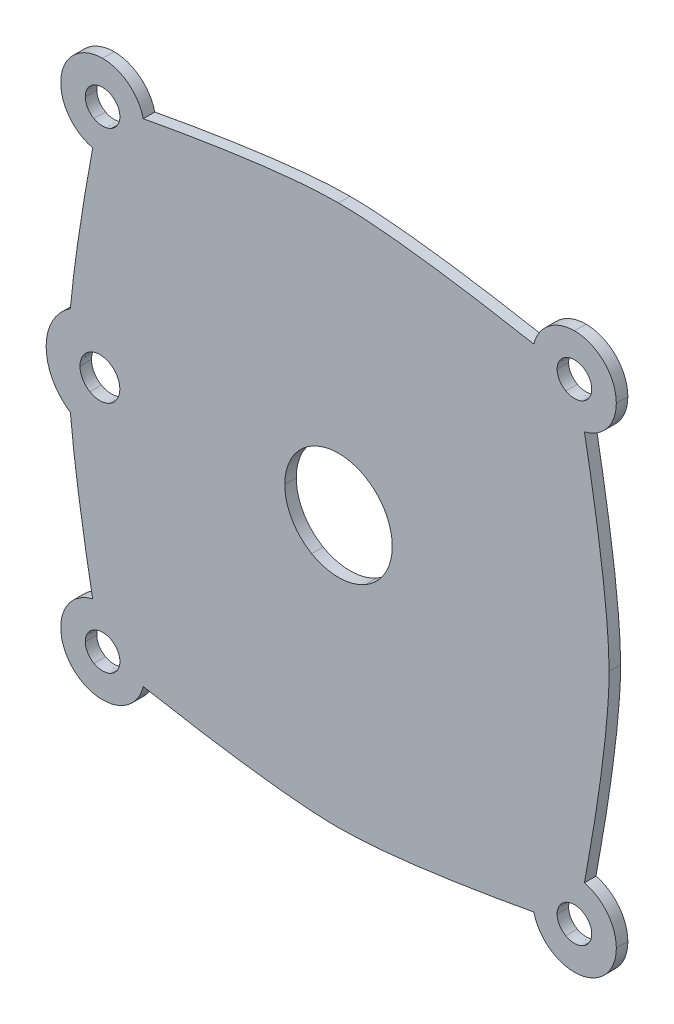
SolidWorks part; units mm, degrees
ref_plane "Front Plane" through (0, 0, 0) normal (0, 0, 1) x (1, 0, 0)
ref_plane "Top Plane" through (0, 0, 0) normal (0, 1, 0) x (1, 0, 0)
ref_plane "Right Plane" through (0, 0, 0) normal (1, 0, 0) x (0, 0, -1)
sketch "Model" plane through (0, 0, 0) normal (0, 0, 1) x (1, 0, 0)
  spline S0 degree 3 poles (51.3556, 215.6759) (48.1704, 215.6759) (45.5877, 213.0932) (45.5877, 209.908) knots 0 0 0 0 1 1 1 1
  spline S1 degree 3 poles (45.5877, 209.908) (45.5877, 207.1926) (47.4617, 204.9204) (49.9886, 204.3076) knots 0 0 0 0 1 1 1 1
  spline S2 degree 3 poles (49.9886, 204.3076) (48.974, 198.8606) (47.5466, 190.5406) (46.9106, 183.5819) knots 0 0 0 0 1 1 1 1
  spline S3 degree 3 poles (46.9106, 183.5819) (44.902, 182.2575) (43.5769, 179.9855) (43.5769, 177.3995) knots 0 0 0 0 1 1 1 1
  spline S4 degree 3 poles (43.5769, 177.3995) (43.5769, 174.8136) (44.902, 172.5327) (46.9106, 171.2083) knots 0 0 0 0 1 1 1 1
  spline S5 degree 3 poles (46.9106, 171.2083) (47.5443, 164.2507) (48.9657, 155.9401) (49.9798, 150.4914) knots 0 0 0 0 1 1 1 1
  spline S6 degree 3 poles (49.9798, 150.4914) (47.4567, 149.8759) (45.5877, 147.6036) (45.5877, 144.891) knots 0 0 0 0 1 1 1 1
  spline S7 degree 3 poles (45.5877, 144.891) (45.5877, 141.7058) (48.1704, 139.1231) (51.3556, 139.1231) knots 0 0 0 0 1 1 1 1
  spline S8 degree 3 poles (51.3556, 139.1231) (54.0682, 139.1231) (56.3405, 140.9922) (56.956, 143.5152) knots 0 0 0 0 1 1 1 1
  spline S9 degree 3 poles (56.956, 143.5152) (64.1681, 142.173) (76.4059, 140.1197) (83.8641, 140.1197) knots 0 0 0 0 1 1 1 1
  spline S10 degree 3 poles (83.8641, 140.1197) (91.3223, 140.1197) (103.5601, 142.173) (110.7722, 143.5152) knots 0 0 0 0 1 1 1 1
  spline S11 degree 3 poles (110.7722, 143.5152) (111.3879, 140.9924) (113.6601, 139.1231) (116.3726, 139.1231) knots 0 0 0 0 1 1 1 1
  spline S12 degree 3 poles (116.3726, 139.1231) (119.5578, 139.1231) (122.1405, 141.7058) (122.1405, 144.891) knots 0 0 0 0 1 1 1 1
  spline S13 degree 3 poles (122.1405, 144.891) (122.1405, 147.6013) (120.2682, 149.8736) (117.7484, 150.4914) knots 0 0 0 0 1 1 1 1
  spline S14 degree 3 poles (117.7484, 150.4914) (119.0906, 157.7035) (121.1439, 169.9413) (121.1439, 177.3995) knots 0 0 0 0 1 1 1 1
  spline S15 degree 3 poles (121.1439, 177.3995) (121.1439, 184.8577) (119.0906, 197.0955) (117.7484, 204.3076) knots 0 0 0 0 1 1 1 1
  spline S16 degree 3 poles (117.7484, 204.3076) (120.268, 204.9255) (122.1405, 207.1978) (122.1405, 209.908) knots 0 0 0 0 1 1 1 1
  spline S17 degree 3 poles (122.1405, 209.908) (122.1405, 213.0932) (119.5578, 215.6759) (116.3726, 215.6759) knots 0 0 0 0 1 1 1 1
  spline S18 degree 3 poles (116.3726, 215.6759) (113.6624, 215.6759) (111.3901, 213.8035) (110.7722, 211.2838) knots 0 0 0 0 1 1 1 1
  spline S19 degree 3 poles (110.7722, 211.2838) (103.5601, 212.626) (91.3223, 214.6793) (83.8641, 214.6793) knots 0 0 0 0 1 1 1 1
  spline S20 degree 3 poles (83.8641, 214.6793) (76.4044, 214.6793) (64.1668, 212.6181) (56.956, 211.275) knots 0 0 0 0 1 1 1 1
  spline S21 degree 3 poles (56.956, 211.275) (56.3413, 213.7991) (54.069, 215.6759) (51.3556, 215.6759) knots 0 0 0 0 1 1 1 1
  spline S22 degree 3 poles (53.7356, 209.9047) (53.7356, 209.0798) (53.2809, 208.3176) (52.5427, 207.9052) knots 0 0 0 0 1 1 1 1
  spline S23 degree 3 poles (52.5427, 207.9052) (51.8045, 207.4928) (50.8951, 207.4928) (50.1569, 207.9052) knots 0 0 0 0 1 1 1 1
  spline S24 degree 3 poles (50.1569, 207.9052) (49.4187, 208.3176) (48.964, 209.0798) (48.964, 209.9047) knots 0 0 0 0 1 1 1 1
  spline S25 degree 3 poles (48.964, 209.9047) (48.964, 210.7295) (49.4187, 211.4917) (50.1569, 211.9041) knots 0 0 0 0 1 1 1 1
  spline S26 degree 3 poles (50.1569, 211.9041) (50.8951, 212.3165) (51.8045, 212.3165) (52.5427, 211.9041) knots 0 0 0 0 1 1 1 1
  spline S27 degree 3 poles (52.5427, 211.9041) (53.2809, 211.4917) (53.7356, 210.7295) (53.7356, 209.9047) knots 0 0 0 0 1 1 1 1
  spline S28 degree 3 poles (118.7541, 144.8861) (118.7541, 144.0613) (118.2994, 143.2991) (117.5612, 142.8867) knots 0 0 0 0 1 1 1 1
  spline S29 degree 3 poles (117.5612, 142.8867) (116.823, 142.4743) (115.9136, 142.4743) (115.1754, 142.8867) knots 0 0 0 0 1 1 1 1
  spline S30 degree 3 poles (115.1754, 142.8867) (114.4373, 143.2991) (113.9825, 144.0613) (113.9825, 144.8861) knots 0 0 0 0 1 1 1 1
  spline S31 degree 3 poles (113.9825, 144.8861) (113.9825, 145.711) (114.4373, 146.4732) (115.1754, 146.8856) knots 0 0 0 0 1 1 1 1
  spline S32 degree 3 poles (115.1754, 146.8856) (115.9136, 147.298) (116.823, 147.298) (117.5612, 146.8856) knots 0 0 0 0 1 1 1 1
  spline S33 degree 3 poles (117.5612, 146.8856) (118.2994, 146.4732) (118.7541, 145.711) (118.7541, 144.8861) knots 0 0 0 0 1 1 1 1
  spline S34 degree 3 poles (53.7356, 144.8861) (53.7356, 144.0613) (53.2809, 143.2991) (52.5427, 142.8867) knots 0 0 0 0 1 1 1 1
  spline S35 degree 3 poles (52.5427, 142.8867) (51.8045, 142.4743) (50.8951, 142.4743) (50.1569, 142.8867) knots 0 0 0 0 1 1 1 1
  spline S36 degree 3 poles (50.1569, 142.8867) (49.4187, 143.2991) (48.964, 144.0613) (48.964, 144.8861) knots 0 0 0 0 1 1 1 1
  spline S37 degree 3 poles (48.964, 144.8861) (48.964, 145.711) (49.4187, 146.4732) (50.1569, 146.8856) knots 0 0 0 0 1 1 1 1
  spline S38 degree 3 poles (50.1569, 146.8856) (50.8951, 147.298) (51.8045, 147.298) (52.5427, 146.8856) knots 0 0 0 0 1 1 1 1
  spline S39 degree 3 poles (52.5427, 146.8856) (53.2809, 146.4732) (53.7356, 145.711) (53.7356, 144.8861) knots 0 0 0 0 1 1 1 1
  spline S40 degree 3 poles (118.7541, 209.9047) (118.7541, 209.0798) (118.2994, 208.3176) (117.5612, 207.9052) knots 0 0 0 0 1 1 1 1
  spline S41 degree 3 poles (117.5612, 207.9052) (116.823, 207.4928) (115.9136, 207.4928) (115.1754, 207.9052) knots 0 0 0 0 1 1 1 1
  spline S42 degree 3 poles (115.1754, 207.9052) (114.4373, 208.3176) (113.9825, 209.0798) (113.9825, 209.9047) knots 0 0 0 0 1 1 1 1
  spline S43 degree 3 poles (113.9825, 209.9047) (113.9825, 210.7295) (114.4373, 211.4917) (115.1754, 211.9041) knots 0 0 0 0 1 1 1 1
  spline S44 degree 3 poles (115.1754, 211.9041) (115.9136, 212.3165) (116.823, 212.3165) (117.5612, 211.9041) knots 0 0 0 0 1 1 1 1
  spline S45 degree 3 poles (117.5612, 211.9041) (118.2994, 211.4917) (118.7541, 210.7295) (118.7541, 209.9047) knots 0 0 0 0 1 1 1 1
  spline S46 degree 3 poles (53.7251, 177.3954) (53.7258, 176.4147) (53.203, 175.5083) (52.3538, 175.0177) knots 0 0 0 0 1 1 1 1
  spline S47 degree 3 poles (52.3538, 175.0177) (51.5046, 174.5272) (50.4582, 174.5272) (49.6091, 175.0177) knots 0 0 0 0 1 1 1 1
  spline S48 degree 3 poles (49.6091, 175.0177) (48.7599, 175.5083) (48.2371, 176.4147) (48.2377, 177.3954) knots 0 0 0 0 1 1 1 1
  spline S49 degree 3 poles (48.2377, 177.3954) (48.2371, 178.3761) (48.7599, 179.2825) (49.6091, 179.7731) knots 0 0 0 0 1 1 1 1
  spline S50 degree 3 poles (49.6091, 179.7731) (50.4582, 180.2636) (51.5046, 180.2636) (52.3538, 179.7731) knots 0 0 0 0 1 1 1 1
  spline S51 degree 3 poles (52.3538, 179.7731) (53.203, 179.2825) (53.7258, 178.3761) (53.7251, 177.3954) knots 0 0 0 0 1 1 1 1
  spline S52 degree 3 poles (91.2645, 177.3954) (91.2663, 174.7485) (89.8552, 172.3019) (87.5632, 170.978) knots 0 0 0 0 1 1 1 1
  spline S53 degree 3 poles (87.5632, 170.978) (85.2712, 169.654) (82.4469, 169.654) (80.1549, 170.978) knots 0 0 0 0 1 1 1 1
  spline S54 degree 3 poles (80.1549, 170.978) (77.8629, 172.3019) (76.4519, 174.7485) (76.4536, 177.3954) knots 0 0 0 0 1 1 1 1
  spline S55 degree 3 poles (76.4536, 177.3954) (76.4519, 180.0423) (77.8629, 182.4889) (80.1549, 183.8128) knots 0 0 0 0 1 1 1 1
  spline S56 degree 3 poles (80.1549, 183.8128) (82.4469, 185.1368) (85.2712, 185.1368) (87.5632, 183.8128) knots 0 0 0 0 1 1 1 1
  spline S57 degree 3 poles (87.5632, 183.8128) (89.8552, 182.4889) (91.2663, 180.0423) (91.2645, 177.3954) knots 0 0 0 0 1 1 1 1
extrude "Boss-Extrude1" add sketch "Model" along normal blind 1.5875 contours S2 S3 S4 S5 S6 S7 S8 S9 S10 S11 S12 S13 S14 S15 S16 S17 S18 S19 S20 S21 S0 S1 | S47 S48 S49 S50 S51 S46 | S54 S55 S56 S57 S52 S53 | S23 S24 S25 S26 S27 S22 | S41 S42 S43 S44 S45 S40 | S29 S30 S31 S32 S33 S28 | S35 S36 S37 S38 S39 S34
